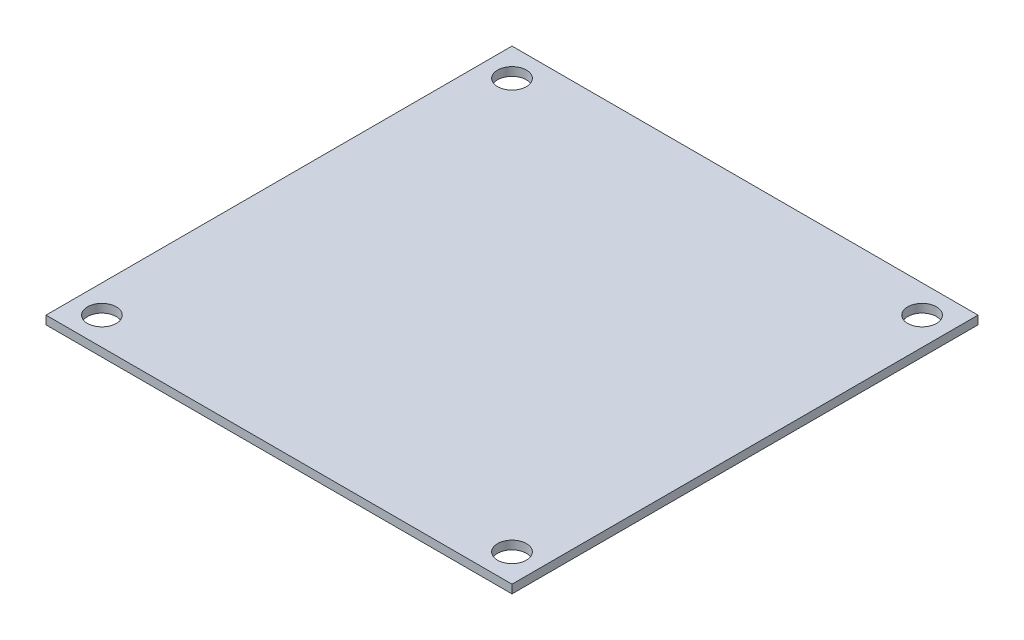
SolidWorks part; units mm, degrees
ref_plane "Front" through (0, 0, 0) normal (0, 0, 1) x (1, 0, 0)
ref_plane "Top" through (0, 0, 0) normal (0, 1, 0) x (1, 0, 0)
ref_plane "Right" through (0, 0, 0) normal (1, 0, 0) x (0, 0, -1)
sketch "Sketch1" plane through (0, 0, 0) normal (0, 1, 0) x (1, 0, 0)
  line L1 (-27.5, -27.5) -> (27.5, -27.5)
  line L2 (-27.5, -27.5) -> (-27.5, 27.5)
  line L3 (-27.5, 27.5) -> (27.5, 27.5)
  line L4 (27.5, -27.5) -> (27.5, 27.5)
  line L5 (-27.5, -27.5) -> (27.5, 27.5) construction
  line L6 (-27.5, 27.5) -> (27.5, -27.5) construction
  point P0 (0, 0)
  dimension "D1" = 55
extrude "Boss-Extrude1" add sketch "Sketch1" along normal mid plane 1
sketch "Sketch2" plane through (0, 0.5, 0) normal (0, 1, 0) x (1, 0, 0)
  line L0 (27.5, -27.5) -> (27.5, 27.5) construction
  line L1 (-27.5, 27.5) -> (-24.2, 27.5) construction
  line L2 (-27.5, 27.5) -> (-27.5, 24.2) construction
  line L3 (-27.5, 24.2) -> (-24.2, 24.2) construction
  line L4 (-24.2, 27.5) -> (-24.2, 24.2) construction
  line L5 (-27.5, -27.5) -> (-24.2, -27.5) construction
  line L6 (-27.5, -27.5) -> (-27.5, -24.2) construction
  line L7 (-27.5, -24.2) -> (-24.2, -24.2) construction
  line L8 (-24.2, -27.5) -> (-24.2, -24.2) construction
  line L9 (27.5, -27.5) -> (24.2, -27.5) construction
  line L10 (27.5, -27.5) -> (27.5, -24.2) construction
  line L11 (27.5, -24.2) -> (24.2, -24.2) construction
  line L12 (24.2, -27.5) -> (24.2, -24.2) construction
  line L14 (27.5, 27.5) -> (24.2, 27.5) construction
  line L15 (27.5, 27.5) -> (27.5, 24.2) construction
  line L16 (27.5, 24.2) -> (24.2, 24.2) construction
  line L17 (24.2, 27.5) -> (24.2, 24.2) construction
  circle A0 centre (-24.2, 24.2) radius 1.7
  circle A1 centre (24.2, 24.2) radius 1.7
  circle A2 centre (-24.2, -24.2) radius 1.7
  circle A3 centre (24.2, -24.2) radius 1.7
  dimension "D2" = 3.4
  dimension "D1" = 3.3
extrude "Cut-Extrude1" cut sketch "Sketch2" against normal through all
